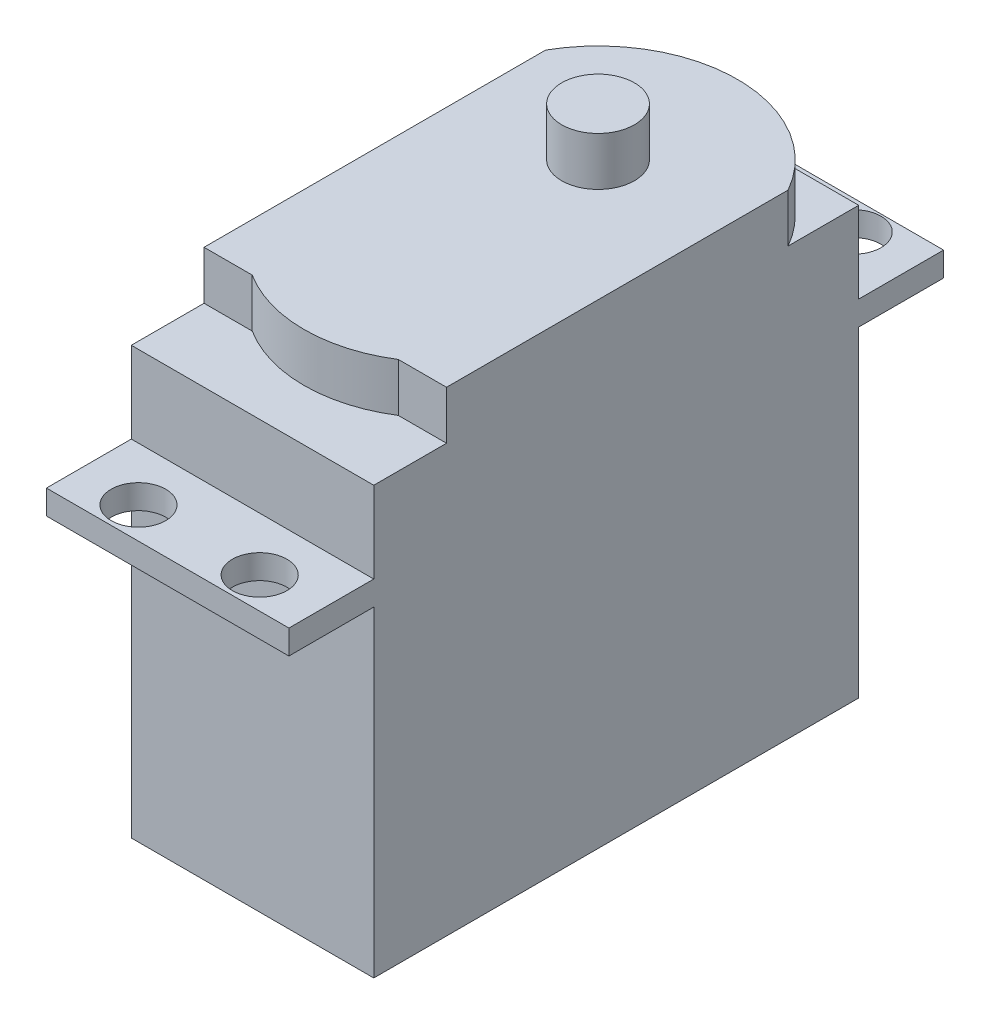
SolidWorks part; units mm, degrees
material "PBT General Purpose"
ref_plane "Front Plane" through (0, 0, 0) normal (0, 0, 1) x (1, 0, 0)
ref_plane "Top Plane" through (0, 0, 0) normal (0, 1, 0) x (1, 0, 0)
ref_plane "Right Plane" through (0, 0, 0) normal (1, 0, 0) x (0, 0, -1)
sketch "Sketch1" plane through (0, 0, 0) normal (1, 0, 0) x (0, 0, -1)
  line L0 (-27, 23.6) -> (27, 23.6) construction
  line L1 (27, 23.6) -> (27, -23.6) construction
  line L2 (27, -23.6) -> (-27, -23.6) construction
  line L3 (-27, -23.6) -> (-27, 23.6) construction
  line L4 (0, -23.6) -> (20, -23.6)
  line L5 (-27, 23.6) -> (27, -23.6) construction
  line L6 (-27, -23.6) -> (27, 23.6) construction
  line L7 (0, -23.6) -> (-20, -23.6)
  line L8 (20, -23.6) -> (20, 4.4)
  line L9 (-20, -23.6) -> (-20, 4.4)
  line L10 (20, 4.4) -> (27, 4.4)
  line L11 (-20, 4.4) -> (-27, 4.4)
  line L12 (27, 4.4) -> (27, 6.4)
  line L13 (27, 6.4) -> (20, 6.4)
  line L14 (20, 6.4) -> (20, 12.4)
  line L15 (-27, 4.4) -> (-27, 6.4)
  line L16 (-27, 6.4) -> (-20, 6.4)
  line L17 (-20, 6.4) -> (-20, 12.4)
  line L18 (-20, 12.4) -> (-20, 23.6)
  line L19 (-20, 23.6) -> (20, 23.6)
  line L20 (20, 23.6) -> (20, 12.4)
  point P0 (0, 0)
  dimension "D1" = 47.2
  dimension "D2" = 54
  dimension "D3" = 40
  dimension "D4" = 28
  dimension "D5" = 2
  dimension "D6" = 6
extrude "Boss-Extrude1" add sketch "Sketch1" along normal blind 20
sketch "Sketch2" plane through (0, 23.6, 0) normal (0, 1, 0) x (1, 0, 0)
  line L1 (0, -20) -> (20, -20)
  line L2 (0, -20) -> (0, 20)
  line L3 (0, 20) -> (20, 20)
  line L4 (20, -20) -> (20, 20)
extrude "Cut-Extrude1" cut sketch "Sketch2" against normal blind 2.5
sketch "Sketch3" plane through (0, 21.1, 0) normal (0, 1, 0) x (1, 0, 0)
  line L0 (10, 27) -> (10, 8.5) construction
  line L2 (20, 27) -> (0, 27) construction
  line L5 (0, 20) -> (20, 20)
  line L6 (0, 20) -> (0, -20)
  line L7 (0, -20) -> (20, -20)
  line L8 (20, 20) -> (20, -20)
  circle A0 centre (10, 8.5) radius 3
  dimension "D2" = 6
  dimension "D1" = 18.5
extrude "Cut-Extrude2" cut sketch "Sketch3" against normal blind 4
sketch "Sketch4" plane through (0, 17.1, 0) normal (0, 1, 0) x (1, 0, 0)
  line L0 (10, -20) -> (10, -14) construction
  line L1 (0, 20) -> (20, 20)
  line L2 (0, 20) -> (0, -14)
  line L3 (10, -20) -> (10, -4.5) construction
  line L4 (20, 20) -> (20, -14)
  line L5 (3.974, -14) -> (0, -14)
  line L6 (16.026, -14) -> (20, -14)
  arc A0 (20, 14.1789) -> (0, 14.1789) centre (10, 8.5) ccw
  arc A1 (3.974, -14) -> (16.026, -14) centre (10, -4.5) ccw
  line M2 (0, 20) -> (0, -20)
  line M3 (0, -20) -> (20, -20)
  line M4 (20, -20) -> (20, 20)
  line M5 (20, 20) -> (0, 20)
  dimension "D3" = 22.5
  dimension "D1" = 6
  dimension "D2" = 15.5
extrude "Cut-Extrude3" cut sketch "Sketch4" against normal blind 4 contours A0 L1 M2 | A0 L4 M5 | A1 L5 L6 M2 M3 M4
sketch "Sketch5" plane through (0, 6.4, 0) normal (0, 1, 0) x (1, 0, 0)
  line L0 (0, 0.0895) -> (10, 0.0895) construction
  line L1 (20, 27) -> (0, 27) construction
  line L2 (10, 0.0895) -> (10, -24.4105) construction
  line L3 (0, 14.1789) -> (0, -14) construction
  line L4 (10, -24.4105) -> (15, -24.4105) construction
  line L5 (10, -24.4105) -> (5, -24.4105) construction
  circle A0 centre (5, -24.4105) radius 2.25
  circle A1 centre (15, -24.4105) radius 2.25
  circle A2 centre (15, 24.5895) radius 2.25
  circle A3 centre (5, 24.5895) radius 2.25
  dimension "D1" = 4.5
  dimension "D2" = 10
  dimension "D3" = 24.5
  dimension "D4" = 10
extrude "Cut-Extrude4" cut sketch "Sketch5" against normal blind 2
chamfer "Chamfer1" distance 1.5 angle 45 4 edges at (10, -23.6, -20) (0, -23.6, 0) (20, -23.6, 0) (10, -23.6, 20)
